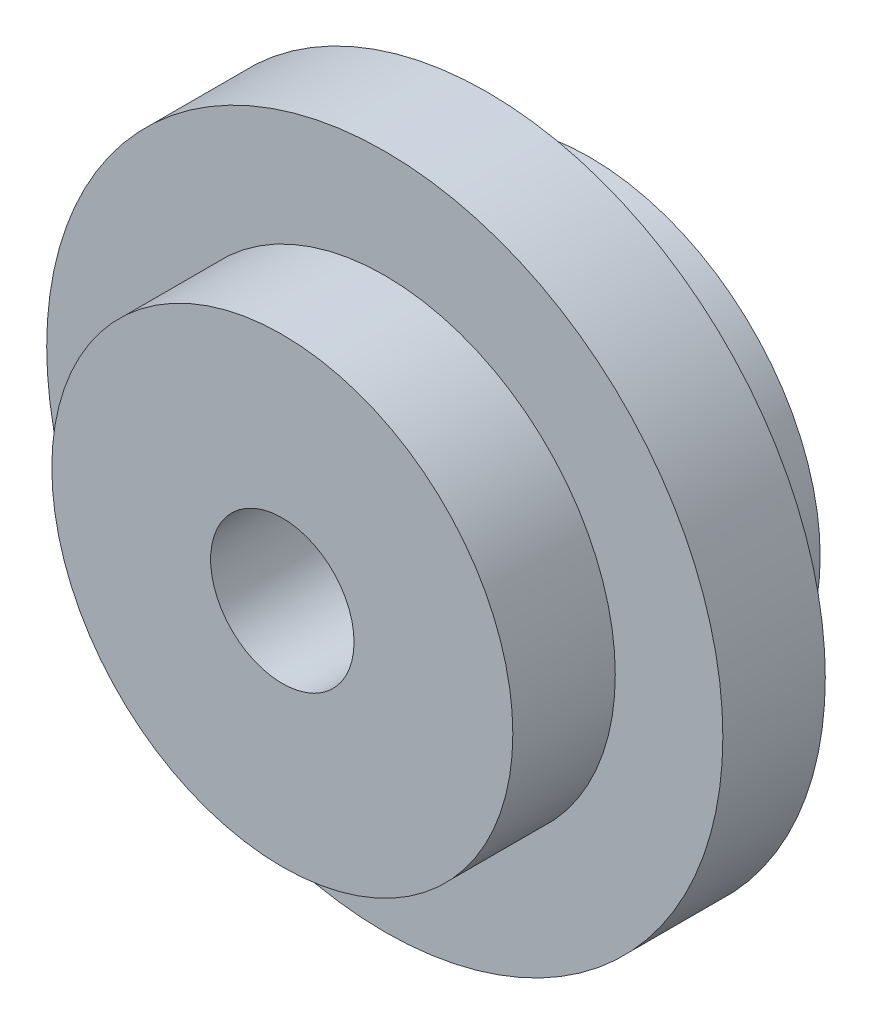
SolidWorks part; units mm, degrees
ref_plane "Front Plane" through (0, 0, 0) normal (0, 0, 1) x (1, 0, 0)
ref_plane "Top Plane" through (0, 0, 0) normal (0, 1, 0) x (1, 0, 0)
ref_plane "Right Plane" through (0, 0, 0) normal (1, 0, 0) x (0, 0, -1)
ref_plane "Plane4" through (0, 0, 33) normal (0, 0, 1) x (1, 0, 0)
sketch "Sketch1" plane through (0, 0, 33) normal (0, 0, 1) x (1, 0, 0)
  circle A0 centre (0, 0) radius 6.6
extrude "Boss-Extrude1" add sketch "Sketch1" against normal blind 2
sketch "Sketch2" plane through (0, 0, 33) normal (0, 0, 1) x (1, 0, 0)
  circle A0 centre (0, 0) radius 4.5
extrude "Boss-Extrude2" add sketch "Sketch2" along normal blind 2 and the other way blind 4
sketch "Sketch3" plane through (0, 0, 33) normal (0, 0, 1) x (1, 0, 0)
  circle A0 centre (0, 0) radius 2
ref_plane "Plane5" through (0, 0, 29) normal (0, 0, 1) x (1, 0, 0)
sketch "Sketch6" plane through (0, 0, 29) normal (0, 0, 1) x (1, 0, 0)
  circle A0 centre (0, 0) radius 1.46
ref_plane "Plane6" through (0, 0, 35) normal (0, 0, 1) x (1, 0, 0)
sketch "Sketch8" plane through (0, 0, 35) normal (0, 0, 1) x (1, 0, 0)
  circle A0 centre (0, 0) radius 1.4
loft "Cut-Loft2" cut profiles "Sketch8", "Sketch6"
